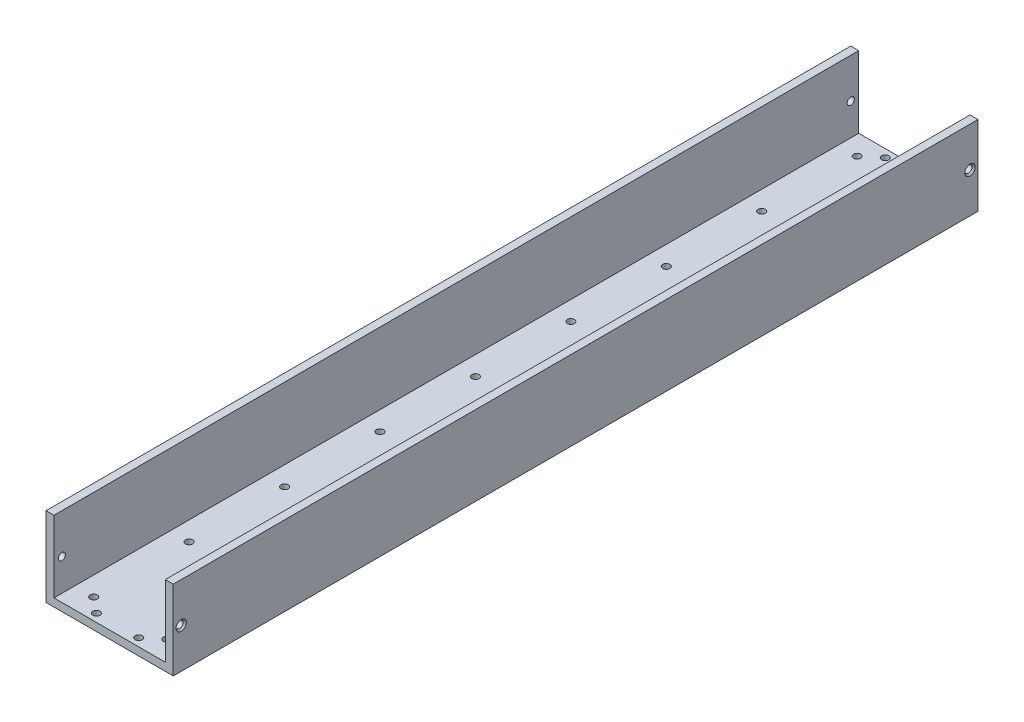
SolidWorks part; units mm, degrees
ref_plane "Piano frontale" through (0, 0, 0) normal (0, 0, 1) x (1, 0, 0)
ref_plane "Piano superiore" through (0, 0, 0) normal (0, 1, 0) x (1, 0, 0)
ref_plane "Piano destro" through (0, 0, 0) normal (1, 0, 0) x (0, 0, -1)
sketch "Schizzo1" plane through (0, 0, 0) normal (0, 0, 1) x (1, 0, 0)
  line L0 (75, 5) -> (75, 50)
  line L1 (0, 0) -> (80, 0)
  line L2 (0, 0) -> (0, 50)
  line L3 (5, 5) -> (75, 5)
  line L4 (80, 0) -> (80, 50)
  line L5 (5, 5) -> (5, 50)
  line L6 (0, 50) -> (5, 50)
  line L7 (75, 50) -> (80, 50)
  dimension "D1" = 50
  dimension "D2" = 80
  dimension "D3" = 5
extrude "Estrusione-Estrusione1" add sketch "Schizzo1" against normal blind 506
sketch "Schizzo2" plane through (80, 0, 0) normal (1, 0, 0) x (0, 0, -1)
  line L0 (0, 50) -> (0, -32.5326) construction
  line L1 (5, 50) -> (5, -32.5326) construction
  line L2 (0, 0) -> (-6.2837, 0) construction
  line L3 (5, 25) -> (-6.2837, 25) construction
  line L4 (0, 25) -> (-6.2837, 25) construction
  dimension "D1" = 5
  dimension "D2" = 25
sketch "Schizzo3" plane through (80, 0, 0) normal (1, 0, 0) x (0, 0, -1)
  line L0 (253, 0) -> (253, 132.3102) construction
  line L1 (506, 0) -> (0, 0) construction
  circle A0 centre (5, 25) radius 2.25
  circle A1 centre (501, 25) radius 2.25
  dimension "D1" = 4.5
extrude "Taglio-Estrusione1" cut sketch "Schizzo3" against normal through all
chamfer "Smusso1" distance 1 angle 45 4 edges at (0, 25, -498.75) (0, 25, -7.25) (80, 25, -498.75) (80, 25, -7.25)
sketch "Schizzo4" plane through (0, 0, 0) normal (0, -1, 0) x (1, 0, 0)
  line L1 (63, 57.5989) -> (63, -521.4906) construction
  line L2 (80, -253) -> (0, -253) construction
  line L4 (40, 0) -> (40, -506) construction
  line L5 (0, 0) -> (80, 0) construction
  line L6 (80, -506) -> (80, 0) construction
  line L13 (0, -506) -> (80, -506) construction
  circle A0 centre (63, -253) radius 2.25
  circle A1 centre (63, -193) radius 2.25
  circle A2 centre (63, -133) radius 2.25
  circle A3 centre (63, -73) radius 2.25
  circle A4 centre (63, -13) radius 2.25
  circle A5 centre (63, -493) radius 2.25
  circle A6 centre (63, -433) radius 2.25
  circle A7 centre (63, -373) radius 2.25
  circle A8 centre (63, -313) radius 2.25
  circle A9 centre (17, -313) radius 2.25
  circle A10 centre (17, -373) radius 2.25
  circle A11 centre (17, -433) radius 2.25
  circle A12 centre (17, -493) radius 2.25
  circle A13 centre (17, -13) radius 2.25
  circle A14 centre (17, -73) radius 2.25
  circle A15 centre (17, -133) radius 2.25
  circle A16 centre (17, -193) radius 2.25
  circle A17 centre (17, -253) radius 2.25
  point P11 (63, -253)
  dimension "D2" = 4.5
  dimension "D1" = 23
  dimension "D3" = 5
extrude "Taglio-Estrusione2" cut sketch "Schizzo4" against normal through all
sketch "Schizzo5" plane through (0, 0, 0) normal (0, -1, 0) x (1, 0, 0)
  line L0 (0, 0) -> (0, 19.2586) construction
  line L1 (26.7, -5) -> (26.7, 19.2586) construction
  line L2 (53.3, -5) -> (53.3, 19.2586) construction
  line L3 (0, 0) -> (94.2259, 0) construction
  line L4 (0, -5) -> (94.2259, -5) construction
  line L5 (26.7, 0) -> (26.7, 19.2586) construction
  line L6 (53.3, 0) -> (53.3, 19.2586) construction
  line L7 (0, -253) -> (-145.0713, -253) construction
  line L8 (0, -506) -> (0, 0) construction
  line L9 (0, -501) -> (94.2259, -501) construction
  line L10 (0, -506) -> (94.2259, -506) construction
  line L11 (53.3, -501) -> (53.3, -525.2586) construction
  line L12 (26.7, -501) -> (26.7, -525.2586) construction
  line L13 (0, -506) -> (0, -525.2586) construction
  circle A0 centre (26.7, -5) radius 2.25
  circle A1 centre (53.3, -5) radius 2.25
  circle A2 centre (53.3, -501) radius 2.25
  circle A3 centre (26.7, -501) radius 2.25
  dimension "D4" = 4.5
  dimension "D5" = 4.5
  dimension "D1" = 26.7
  dimension "D2" = 53.3
  dimension "D3" = 5
extrude "Taglio-Estrusione3" cut sketch "Schizzo5" against normal through all
chamfer "Smusso2" distance 1 angle 45 4 edges at (53.3, 0, -498.75) (26.7, 0, -498.75) (53.3, 0, -7.25) (26.7, 0, -7.25)
